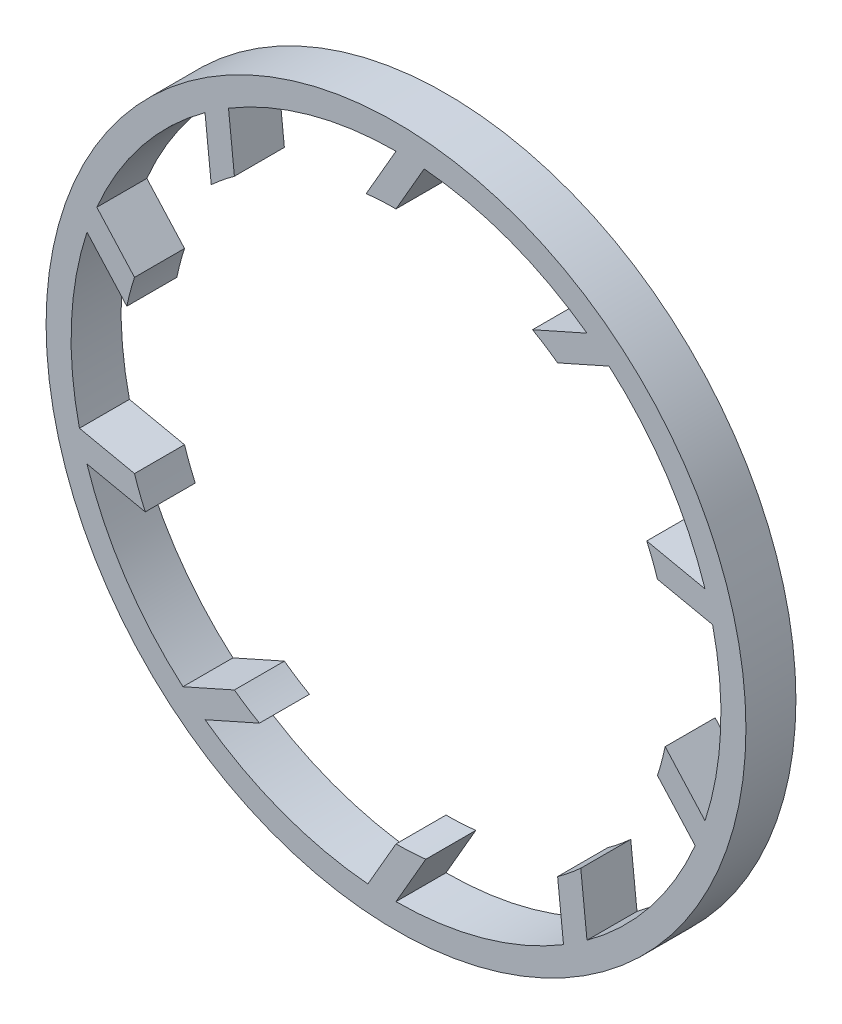
SolidWorks part; units mm, degrees
ref_plane "Front Plane" through (0, 0, 0) normal (0, 0, 1) x (1, 0, 0)
ref_plane "Top Plane" through (0, 0, 0) normal (0, 1, 0) x (1, 0, 0)
ref_plane "Right Plane" through (0, 0, 0) normal (1, 0, 0) x (0, 0, -1)
sketch "Sketch1" plane through (0, 0, 0) normal (0, 0, 1) x (1, 0, 0)
  line L0 (-1000, 0) -> (49000, 0) construction
  line L1 (0, -1000) -> (0, 49000) construction
  line L2 (0, 32.5) -> (-2.9803, 27.338)
  line L3 (0, 27.5) -> (2.8162, 32.3778)
  line L4 (19.103, 26.2931) -> (13.6578, 23.8687)
  line L5 (16.1641, 22.248) -> (21.3095, 24.5389)
  line L6 (30.9093, 10.0431) -> (25.0791, 11.2823)
  line L7 (26.1541, 8.498) -> (31.6633, 7.3269)
  line L8 (30.9093, -10.0431) -> (26.921, -5.6135)
  line L9 (26.1541, -8.498) -> (29.9228, -12.6836)
  line L10 (19.103, -26.2931) -> (18.48, -20.3652)
  line L11 (16.1641, -22.248) -> (16.7528, -27.8495)
  line L12 (0, -32.5) -> (2.9803, -27.338)
  line L13 (0, -27.5) -> (-2.8162, -32.3778)
  line L14 (-19.103, -26.2931) -> (-13.6578, -23.8687)
  line L15 (-16.1641, -22.248) -> (-21.3095, -24.5389)
  line L16 (-30.9093, -10.0431) -> (-25.0791, -11.2823)
  line L17 (-26.1541, -8.498) -> (-31.6633, -7.3269)
  line L18 (-30.9093, 10.0431) -> (-26.921, 5.6135)
  line L19 (-26.1541, 8.498) -> (-29.9228, 12.6836)
  line L20 (-19.103, 26.2931) -> (-18.48, 20.3652)
  line L21 (-16.1641, 22.248) -> (-16.7528, 27.8495)
  circle A0 centre (0, 0) radius 35
  arc A1 (30.9093, -10.0431) -> (31.6633, 7.3269) centre (0, 0) ccw
  arc A2 (-16.1641, 22.248) -> (-18.48, 20.3652) centre (0, 0) ccw
  arc A3 (0, 27.5) -> (-2.9803, 27.338) centre (0, 0) ccw
  arc A4 (16.1641, 22.248) -> (13.6578, 23.8687) centre (0, 0) ccw
  arc A5 (26.1541, 8.498) -> (25.0791, 11.2823) centre (0, 0) ccw
  arc A6 (-26.1541, 8.498) -> (-26.921, 5.6135) centre (0, 0) ccw
  arc A7 (-26.1541, -8.498) -> (-25.0791, -11.2823) centre (0, 0) ccw
  arc A8 (-16.1641, -22.248) -> (-13.6578, -23.8687) centre (0, 0) ccw
  arc A9 (0, -27.5) -> (2.9803, -27.338) centre (0, 0) ccw
  arc A10 (16.1641, -22.248) -> (18.48, -20.3652) centre (0, 0) ccw
  arc A11 (26.1541, -8.498) -> (26.921, -5.6135) centre (0, 0) ccw
  arc A12 (30.9093, 10.0431) -> (21.3095, 24.5389) centre (0, 0) ccw
  arc A13 (19.103, 26.2931) -> (2.8162, 32.3778) centre (0, 0) ccw
  arc A14 (0, 32.5) -> (-16.7528, 27.8495) centre (0, 0) ccw
  arc A15 (-19.103, 26.2931) -> (-29.9228, 12.6836) centre (0, 0) ccw
  arc A16 (-30.9093, 10.0431) -> (-31.6633, -7.3269) centre (0, 0) ccw
  arc A17 (-30.9093, -10.0431) -> (-21.3095, -24.5389) centre (0, 0) ccw
  arc A18 (-19.103, -26.2931) -> (-2.8162, -32.3778) centre (0, 0) ccw
  arc A19 (0, -32.5) -> (16.7528, -27.8495) centre (0, 0) ccw
  arc A20 (19.103, -26.2931) -> (29.9228, -12.6836) centre (0, 0) ccw
  point P53 (0, 0)
  dimension "D1" = 70
  dimension "D2" = 65
  dimension "D3" = 55
  dimension "D4" = 30
  dimension "D5" = 10
extrude "Boss-Extrude2" add sketch "Sketch1" along normal mid plane 5
scale "Scale1" scale about centroid uniform scaling yes scale factor 1.5
